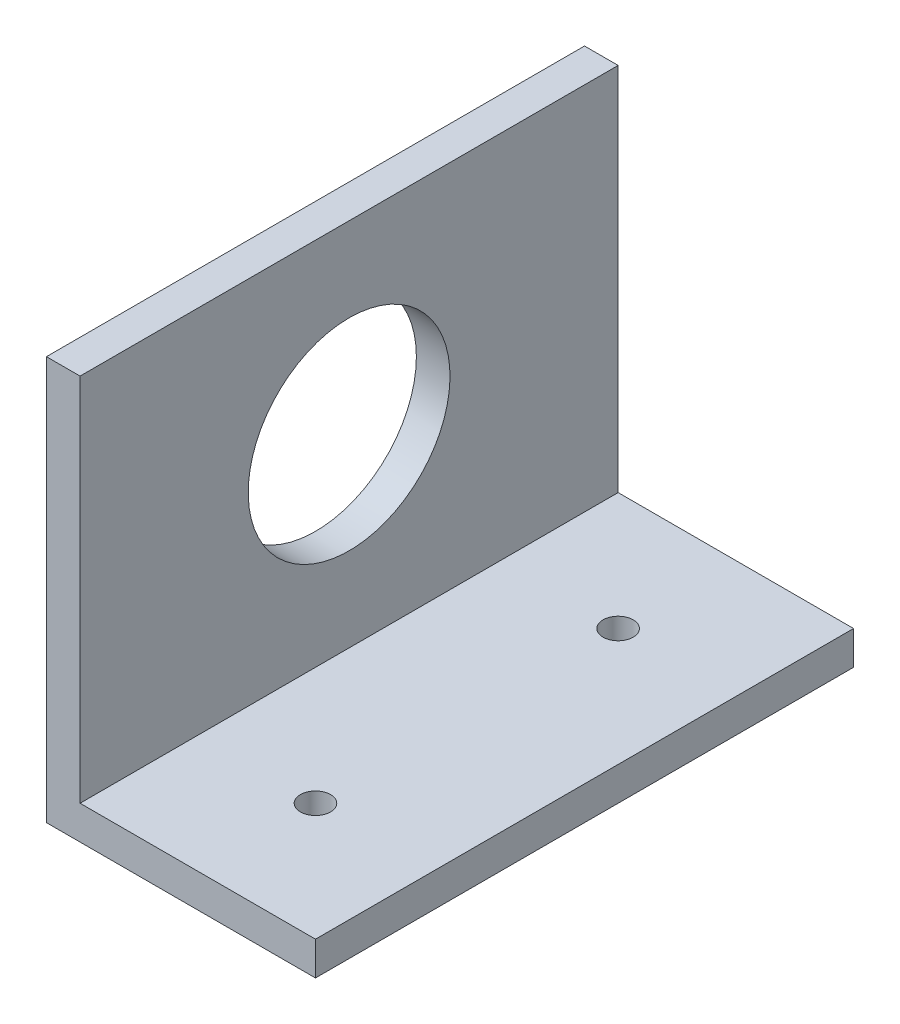
SolidWorks part; units mm, degrees
material "6061-T6 (SS)"
ref_plane "Front Plane" through (0, 0, 0) normal (0, 0, 1) x (1, 0, 0)
ref_plane "Top Plane" through (0, 0, 0) normal (0, 1, 0) x (1, 0, 0)
ref_plane "Right Plane" through (0, 0, 0) normal (1, 0, 0) x (0, 0, -1)
sketch "Sketch1" plane through (0, 0, 0) normal (0, 0, 1) x (1, 0, 0)
  line L0 (25.4, 0) -> (0, 0)
  line L1 (0, 0) -> (0, 38.1)
  line L2 (0, 38.1) -> (3.175, 38.1)
  line L3 (3.175, 38.1) -> (3.175, 3.175)
  line L4 (3.175, 3.175) -> (25.4, 3.175)
  line L5 (25.4, 3.175) -> (25.4, 0)
  dimension "D1" = 38.1
  dimension "D2" = 25.4
  dimension "D3" = 3.175
extrude "Boss-Extrude1" add sketch "Sketch1" along normal blind 50.8
sketch "Sketch2" plane through (3.175, 0, 0) normal (1, 0, 0) x (0, 0, -1)
  line L2 (-25.4, 20.6375) -> (-25.4, 38.1) construction
  line L3 (-50.8, 38.1) -> (0, 38.1) construction
  circle A0 centre (-25.4, 20.6375) radius 9.525
  dimension "D1" = 19.05
  dimension "D2" = 17.4625
extrude "Cut-Extrude1" cut sketch "Sketch2" against normal blind 50.8
sketch "Sketch3" plane through (0, 3.175, 0) normal (0, 1, 0) x (1, 0, 0)
  line L0 (25.4, 0) -> (3.175, 0) construction
  line L1 (0, -50.8) -> (0, 0) construction
  line L2 (25.4, -50.8) -> (3.175, -50.8) construction
  circle A0 centre (14.2875, -11.1125) radius 1.4224
  circle A1 centre (14.2875, -39.6875) radius 1.4224
  dimension "D1" = 2.8448
  dimension "D2" = 11.1125
  dimension "D3" = 11.1125
  dimension "D4" = 14.2875
extrude "Cut-Extrude2" cut sketch "Sketch3" against normal through all
sketch "Sketch4" plane through (0, 3.175, 0) normal (0, 1, 0) x (1, 0, 0)
  line L0 (3.175, -50.8) -> (3.175, 0) construction
  line L1 (3.175, -15.5575) -> (25.4, -15.5575)
  line L2 (3.175, -15.5575) -> (3.175, -35.2425)
  line L3 (3.175, -35.2425) -> (25.4, -35.2425)
  line L4 (25.4, -15.5575) -> (25.4, -35.2425)
  line L5 (25.4, -50.8) -> (25.4, 0) construction
  circle A0 centre (14.2875, -11.1125) radius 1.4224 construction
  circle A1 centre (14.2875, -39.6875) radius 1.4224 construction
  dimension "D1" = 4.445
  dimension "D2" = 4.445
extrude "Cut-Extrude3" [suppressed] cut sketch "Sketch4" against normal blind 3.175
